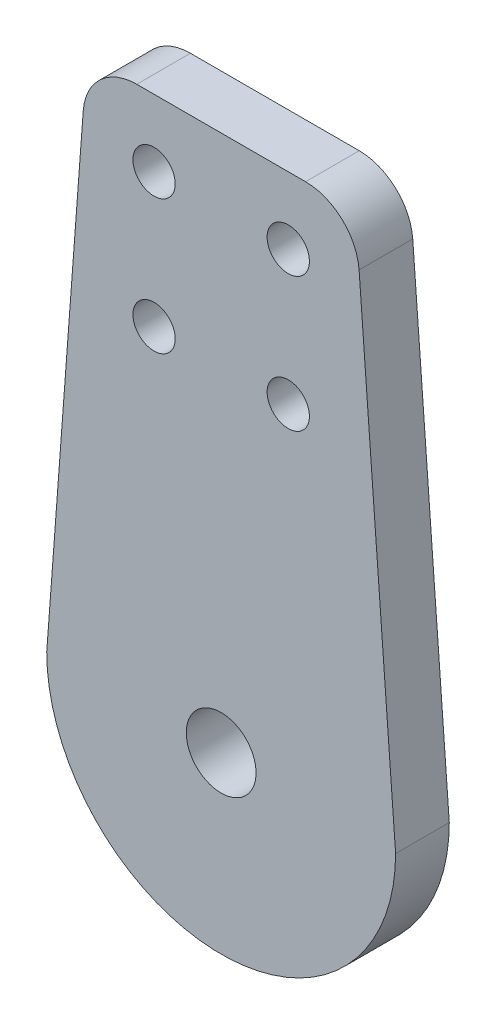
SolidWorks part; units mm, degrees
ref_plane "前视基准面" through (0, 0, 0) normal (0, 0, 1) x (1, 0, 0)
ref_plane "上视基准面" through (0, 0, 0) normal (0, 1, 0) x (1, 0, 0)
ref_plane "右视基准面" through (0, 0, 0) normal (1, 0, 0) x (0, 0, -1)
other "Configuration Table"
sketch "草图1" plane through (0, 0, 0) normal (0, 0, 1) x (1, 0, 0)
  line L1 (0, 0) -> (20, 0)
  line L2 (0, 0) -> (0, -40)
  line L3 (0, -40) -> (20, -40)
  line L4 (20, 0) -> (20, -40)
  dimension "D1" = 20
  dimension "D2" = 40
extrude "凸台-拉伸1" add sketch "草图1" along normal blind 4
sketch "草图5" plane through (0, 0, 4) normal (0, 0, 1) x (1, 0, 0)
  line L0 (10, 0) -> (10, -10) construction
  line L1 (20, 0) -> (0, 0) construction
  line L2 (10, -10) -> (0, -10) construction
  line L3 (0, 0) -> (0, -40) construction
  circle A0 centre (5, -5) radius 1.575
  circle A1 centre (15, -5) radius 1.575
  circle A2 centre (15, -15) radius 1.575
  circle A3 centre (5, -15) radius 1.575
  dimension "D1" = 3.15
  dimension "D2" = 5
  dimension "D3" = 5
  dimension "D4" = 10
extrude "切除-拉伸2" cut sketch "草图5" against normal through all
sketch "草图10" plane through (0, 0, 0) normal (0, 0, -1) x (-1, 0, 0)
  line L0 (-20, 0) -> (-20, -40)
  line L1 (-20, -40) -> (-23, -40)
  line L2 (-23, -40) -> (-20, 0)
  line L3 (-10, 0) -> (-10, -40) construction
  line L4 (-20, 0) -> (0, 0) construction
  line L5 (0, -40) -> (-20, -40) construction
  line L6 (3, -40) -> (0, 0)
  line L7 (0, -40) -> (3, -40)
  line L8 (0, 0) -> (0, -40)
  line L9 (3, -40) -> (-23, -40)
  arc A0 (-23, -40) -> (3, -40) centre (-10, -40) ccw
  line M7 (0, -40) -> (0, 0)
  line M9 (-20, 0) -> (-20, -40)
  line M10 (-20, -40) -> (0, -40)
  dimension "D1" = 3
extrude "凸台-拉伸2" add sketch "草图10" along direction (0, 0, 1) on the side against the normal up to surface (4 mm away) contours L2 L1 M9 | L7 L6 M7 | L1 A0 L7 L9 M10
sketch "草图11" plane through (0, 0, 0) normal (0, 0, -1) x (-1, 0, 0)
  circle A0 centre (-10, -40) radius 2.6
  dimension "D1" = 5.2
extrude "切除-拉伸3" cut sketch "草图11" against normal through all
fillet "圆角1" radius 4 2 edges at (20, 0, 2) (0, 0, 2)
